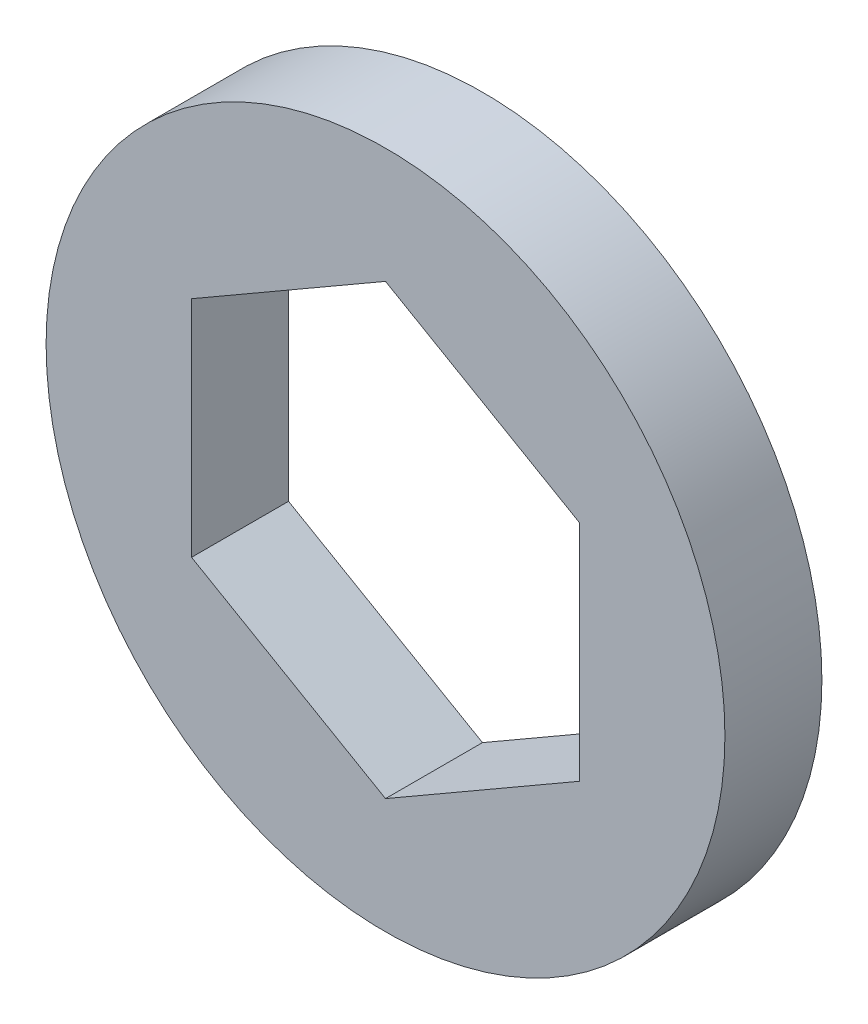
SolidWorks part; units mm, degrees
material "Nylon 101"
ref_plane "Front Plane" through (0, 0, 0) normal (0, 0, 1) x (1, 0, 0)
ref_plane "Top Plane" through (0, 0, 0) normal (0, 1, 0) x (1, 0, 0)
ref_plane "Right Plane" through (0, 0, 0) normal (1, 0, 0) x (0, 0, -1)
sketch "Sketch1" plane through (0, 0, 0) normal (0, 0, 1) x (1, 0, 0)
  line L1 (0, 7.3323) -> (-6.35, 3.6662)
  line L2 (-6.35, 3.6662) -> (-6.35, -3.6662)
  line L3 (-6.35, -3.6662) -> (0, -7.3323)
  line L4 (0, -7.3323) -> (6.35, -3.6662)
  line L5 (6.35, -3.6662) -> (6.35, 3.6662)
  line L6 (6.35, 3.6662) -> (0, 7.3323)
  circle A0 centre (0, 0) radius 11.1125
  circle A1 centre (0, 0) radius 6.35 construction
  dimension "D1" = 12.7
  dimension "D2" = 22.225
extrude "Boss-Extrude1" add sketch "Sketch1" along normal blind 3.175
